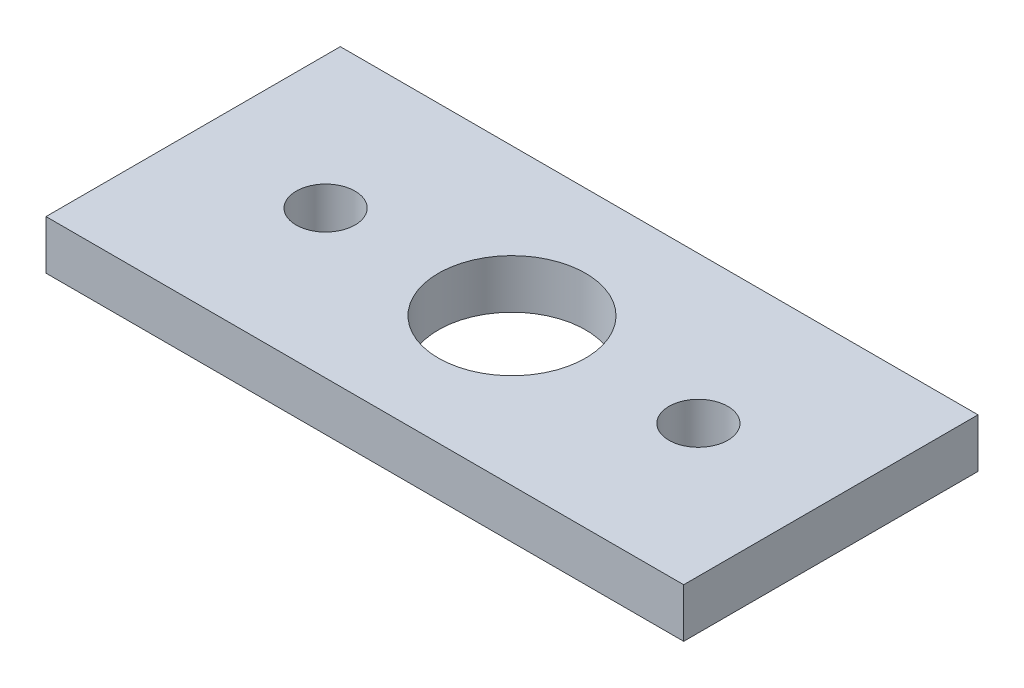
SolidWorks part; units mm, degrees
ref_plane "Front Plane" through (0, 0, 0) normal (0, 0, 1) x (1, 0, 0)
ref_plane "Top Plane" through (0, 0, 0) normal (0, 1, 0) x (1, 0, 0)
ref_plane "Right Plane" through (0, 0, 0) normal (1, 0, 0) x (0, 0, -1)
sketch "Sketch1" plane through (0, 0, 0) normal (0, 1, 0) x (1, 0, 0)
  line L0 (0, 15) -> (65, 15) construction
  line L1 (0, 0) -> (65, 0)
  line L2 (0, 0) -> (0, 30)
  line L3 (0, 30) -> (65, 30)
  line L4 (65, 0) -> (65, 30)
  line L5 (65, 15) -> (32.5, 15) construction
  line L6 (32.5, 15) -> (32.5, 30) construction
  line L7 (32.5, 30) -> (32.5, 0) construction
  circle A0 centre (32.5, 15) radius 7.5
  circle A1 centre (13.5, 15) radius 3
  circle A2 centre (51.5, 15) radius 3
  dimension "D4" = 6
  dimension "D5" = 15
  dimension "D1" = 30
  dimension "D2" = 65
  dimension "D3" = 19
extrude "Boss-Extrude1" add sketch "Sketch1" along normal blind 5
